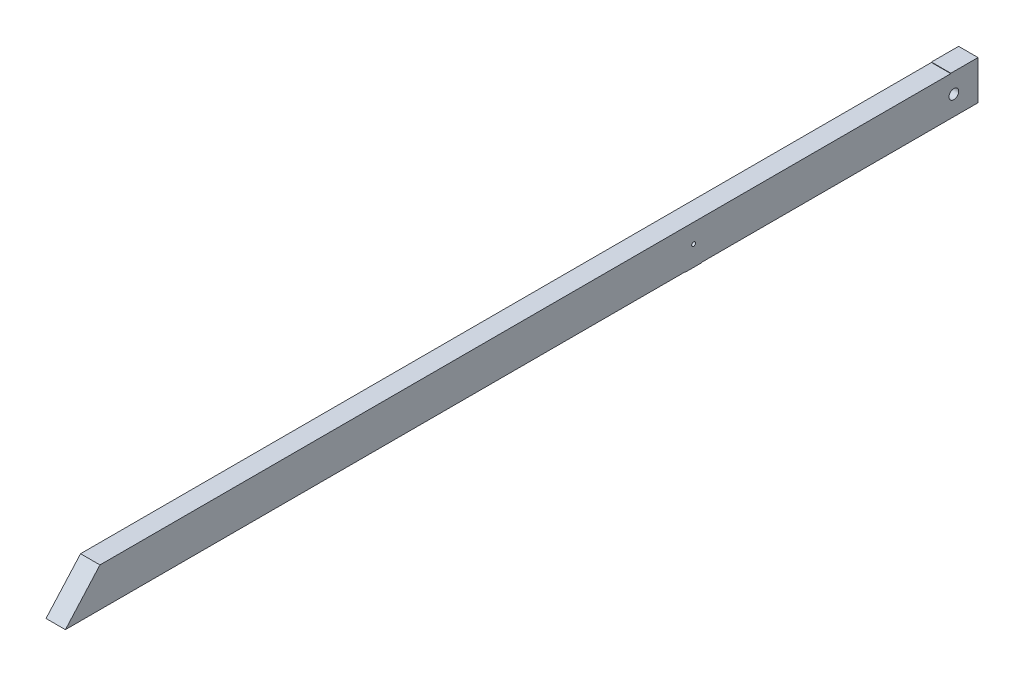
SolidWorks part; units mm, degrees
ref_plane "Front Plane" through (0, 0, 0) normal (0, 0, 1) x (1, 0, 0)
ref_plane "Top Plane" through (0, 0, 0) normal (0, 1, 0) x (1, 0, 0)
ref_plane "Right Plane" through (0, 0, 0) normal (1, 0, 0) x (0, 0, -1)
sketch "Sketch1" plane through (0, 0, 0) normal (0, 0, 1) x (1, 0, 0)
  line L1 (0, 0) -> (50, 0)
  line L2 (0, 0) -> (0, 100)
  line L3 (0, 100) -> (50, 100)
  line L4 (50, 0) -> (50, 100)
  dimension "D1" = 50
  dimension "D2" = 100
extrude "Boss-Extrude1" add sketch "Sketch1" along normal blind 2262.74
sketch "Sketch2" plane through (0, 100, 0) normal (0, 1, 0) x (1, 0, 0)
  line L0 (50, -2262.74) -> (50, 0) construction
  line L1 (0, 0) -> (50, 0)
  line L2 (0, 0) -> (0, -70.0271)
  line L3 (0, -70.0271) -> (50, -70.0271)
  line L4 (50, 0) -> (50, -70.0271)
extrude "Boss-Extrude2" add sketch "Sketch2" along normal blind 1
sketch "Sketch3" plane through (0, 0, 0) normal (0, -1, 0) x (1, 0, 0)
  line L0 (0, 2262.74) -> (0, 0) construction
  line L1 (0, 711.5365) -> (50, 711.5365)
  line L2 (0, 711.5365) -> (0, 754.24)
  line L3 (0, 754.24) -> (50, 754.24)
  line L4 (50, 711.5365) -> (50, 754.24)
  line L5 (50, 2262.74) -> (50, 0) construction
  line L6 (0, 0) -> (50, 0) construction
  dimension "D1" = 754.24
extrude "Boss-Extrude3" add sketch "Sketch3" along normal blind 1
sketch "Sketch4" plane through (50, 0, 0) normal (1, 0, 0) x (0, 0, -1)
  line L0 (-732.8882, -15.1691) -> (-732.8882, 145.6704) construction
  circle A0 centre (-732.8882, 51.0589) radius 5
  dimension "D1" = 10
extrude "Cut-Extrude1" cut sketch "Sketch4" against normal blind 309
sketch "Sketch7" plane through (0, 0, 0) normal (-1, 0, 0) x (0, 0, 1)
  line L0 (0, 50.5) -> (124.5389, 50.5) construction
  line L1 (0, 101) -> (0, 0) construction
  circle A0 centre (62.2695, 50.5) radius 12.5
  dimension "D1" = 25
extrude "Cut-Extrude2" cut sketch "Sketch7" against normal blind 100
sketch "Sketch8" plane through (50, 0, 0) normal (1, 0, 0) x (0, 0, -1)
  line L0 (-2262.74, 0) -> (-2351.7649, 0)
  line L1 (-2351.7649, 0) -> (-2262.74, 100)
  line L2 (-2262.74, 100) -> (-2262.74, 0)
extrude "Boss-Extrude5" add sketch "Sketch8" against normal blind 50
